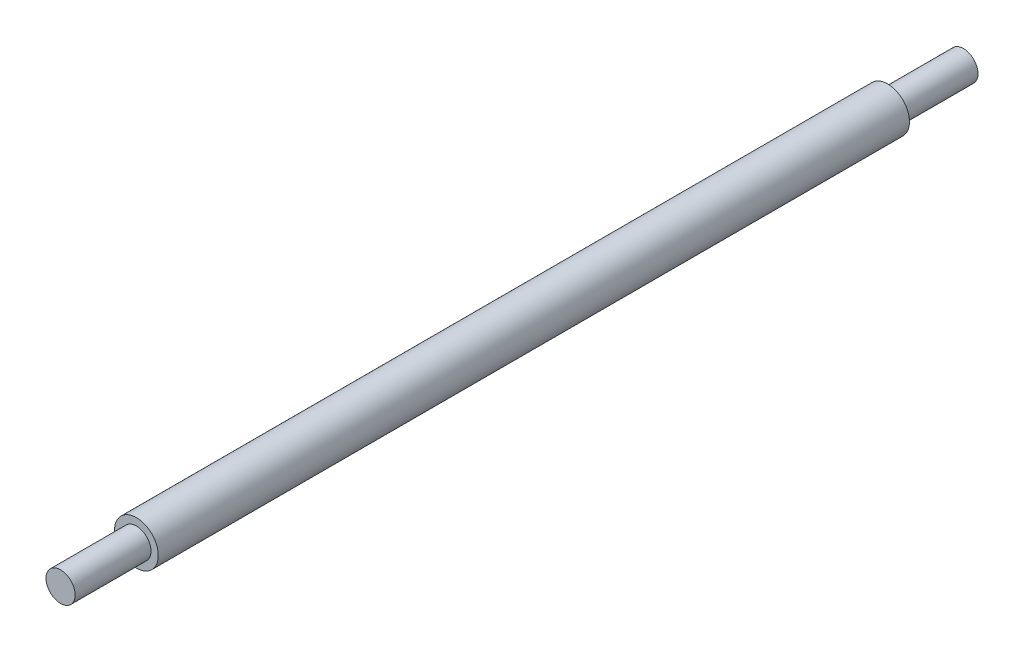
SolidWorks part; units mm, degrees
material "6061 Alloy"
ref_plane "Front" through (0, 0, 0) normal (0, 0, 1) x (1, 0, 0)
ref_plane "Top" through (0, 0, 0) normal (0, 1, 0) x (1, 0, 0)
ref_plane "Right" through (0, 0, 0) normal (1, 0, 0) x (0, 0, -1)
sketch "Sketch1" plane through (0, 0, 0) normal (0, 0, 1) x (1, 0, 0)
  circle A0 centre (0, 0) radius 9.525
  dimension "D1" = 19.05
extrude "Boss-Extrude1" add sketch "Sketch1" along normal blind 327.025
sketch "Sketch2" plane through (0, 0, 327.025) normal (0, 0, 1) x (1, 0, 0)
  circle A0 centre (0, 0) radius 6.35
  dimension "D1" = 12.7
extrude "Boss-Extrude2" add sketch "Sketch2" along normal blind 33.02
sketch "Sketch3" plane through (0, 0, 0) normal (0, 0, -1) x (-1, 0, 0)
  circle A0 centre (0, 0) radius 6.35
  dimension "D1" = 12.7
extrude "Boss-Extrude3" add sketch "Sketch3" along normal blind 33.02
